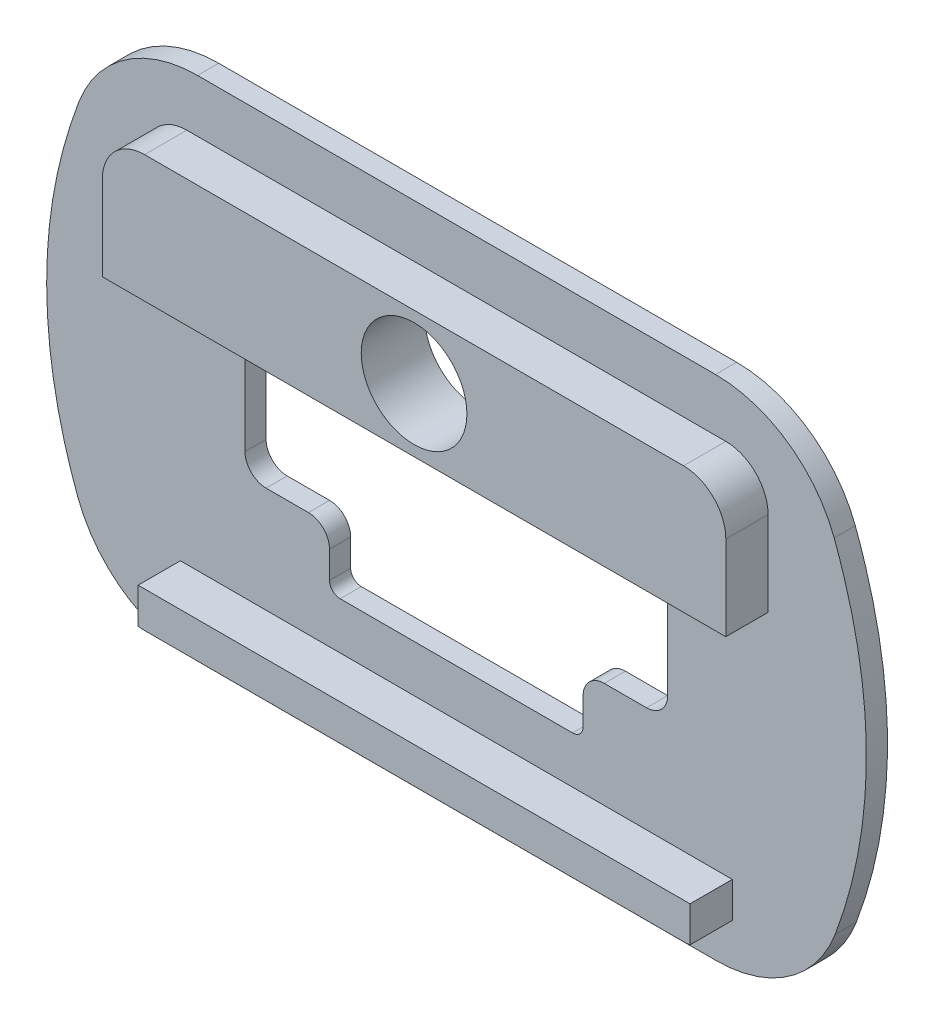
SolidWorks part; units mm, degrees
ref_plane "Front Plane" through (0, 0, 0) normal (0, 0, 1) x (1, 0, 0)
ref_plane "Top Plane" through (0, 0, 0) normal (0, 1, 0) x (1, 0, 0)
ref_plane "Right Plane" through (0, 0, 0) normal (1, 0, 0) x (0, 0, -1)
sketch "Sketch1" plane through (0, 0, 0) normal (0, 0, 1) x (1, 0, 0)
  line L0 (-11.9284, 3.1923) -> (13.5716, 3.1923)
  line L1 (-13.9284, 6.9272) -> (-13.9284, 20.6923)
  line L2 (-11.9284, 22.6923) -> (13.5716, 22.6923)
  line L3 (15.5716, 6.9272) -> (15.5716, 20.6923)
  line L4 (-13.9284, 22.6923) -> (0.9376, 12.8656) construction
  line L7 (-17.0825, 24.7341) -> (-13.2392, 22.2028) construction
  line L8 (0.8216, 1.1923) -> (0.8216, 25.1923) construction
  line L9 (0.8216, 25.1923) -> (0.8216, 3.1923) construction
  line L10 (14.5325, 3.8791) -> (15.5716, 3.1923) construction
  line L11 (0.9376, 12.8656) -> (17.6599, 1.8519) construction
  line L28 (-13.9284, 6.9272) -> (-12.7351, 6.9272)
  line L34 (0.8216, 21.9694) -> (0.8216, 1.9694) construction
  line L35 (-12.2351, 6.4272) -> (-12.2351, 3.2159)
  line L37 (15.5716, 6.9272) -> (14.3784, 6.9272)
  line L38 (13.8784, 6.4272) -> (13.8784, 3.2159)
  arc A0 (13.8784, 3.2159) -> (13.5716, 3.1923) centre (13.5716, 5.1923) cw
  arc A1 (-12.2351, 3.2159) -> (-11.9284, 3.1923) centre (-11.9284, 5.1923) ccw
  arc A2 (-11.9284, 22.6923) -> (-13.9284, 20.6923) centre (-11.9284, 20.6923) ccw
  arc A3 (13.5716, 22.6923) -> (15.5716, 20.6923) centre (13.5716, 20.6923) cw
  arc A18 (-12.7351, 6.9272) -> (-12.2351, 6.4272) centre (-12.7351, 6.4272) cw
  arc A19 (14.3784, 6.9272) -> (13.8784, 6.4272) centre (14.3784, 6.4272) ccw
  point P20 (-12.2351, 22.6923)
  dimension "D5" = 2
  dimension "D6" = 0.5
  dimension "D2" = 29.5
  dimension "D4" = 19.5
sketch "Sketch2" plane through (0, 0, 0) normal (0, 0, 1) x (1, 0, 0)
  line L0 (-4.6784, 7.121) -> (6.3216, 7.121)
  line L1 (-8.1784, 15.9243) -> (9.8216, 15.9243)
  line L2 (-5.1784, 7.621) -> (-5.1784, 8.901)
  line L3 (-9.1784, 14.9243) -> (-9.1784, 10.901)
  line L4 (-8.1784, 9.901) -> (-6.1784, 9.901)
  line L5 (9.8216, 9.901) -> (7.8216, 9.901)
  line L6 (10.8216, 14.9243) -> (10.8216, 10.901)
  line L7 (6.8216, 7.621) -> (6.8216, 8.901)
  line L8 (0.8216, 15.9243) -> (0.8216, 7.121) construction
  line L9 (10.8216, 12.9126) -> (-9.1784, 12.9126) construction
  arc A0 (-5.1784, 8.901) -> (-6.1784, 9.901) centre (-6.1784, 8.901) ccw
  arc A1 (7.8216, 9.901) -> (6.8216, 8.901) centre (7.8216, 8.901) ccw
  arc A2 (-9.1784, 10.901) -> (-8.1784, 9.901) centre (-8.1784, 10.901) ccw
  arc A3 (9.8216, 9.901) -> (10.8216, 10.901) centre (9.8216, 10.901) ccw
  arc A4 (-9.1784, 14.9243) -> (-8.1784, 15.9243) centre (-8.1784, 14.9243) cw
  arc A5 (9.8216, 15.9243) -> (10.8216, 14.9243) centre (9.8216, 14.9243) cw
  arc A6 (-4.6784, 7.121) -> (-5.1784, 7.621) centre (-4.6784, 7.621) cw
  arc A7 (6.8216, 7.621) -> (6.3216, 7.121) centre (6.3216, 7.621) cw
  point P0 (3.0945, 14.452)
  point P1 (3.0945, 14.452)
  point P3 (3.0945, 14.452)
  point P5 (0.8216, 7.121)
  point P8 (0.8216, 15.9243)
  point P17 (0.8216, 12.9126)
  point P18 (0, 0)
  point P22 (0, 0)
  point P30 (-9.1784, 15.9243)
  point P33 (10.8216, 15.9243)
  point P34 (0, 0)
  point P39 (0, 0)
  dimension "D2" = 1
  dimension "D3" = 0.5
  dimension "D1" = 20
sketch "Sketch4" plane through (0, 0, 0) normal (0, 0, 1) x (1, 0, 0)
  line L0 (-11.47, 1.1896) -> (13.1295, 1.1896)
  line L1 (-11.4218, 25.1896) -> (13.0813, 25.1896)
  arc A0 (-11.4218, 25.1896) -> (-17.0387, 21.2993) centre (-11.4218, 19.1896) ccw
  arc A1 (-11.47, 1.1896) -> (-17.0866, 5.0793) centre (-11.47, 7.1896) cw
  arc A2 (13.0813, 25.1896) -> (18.6982, 21.2993) centre (13.0813, 19.1896) cw
  arc A3 (13.1295, 1.1896) -> (18.7461, 5.0793) centre (13.1295, 7.1896) ccw
  spline S0 degree 3 poles (-17.0866, 5.0793) (-18.0777, 7.717) (-19.0613, 13.218) (-18.0465, 18.6161) (-17.0387, 21.2993) knots 0.167422 0.167422 0.167422 0.167422 0.502499 0.837905 0.837905 0.837905 0.837905
  spline S1 degree 3 poles (18.7461, 5.0793) (19.7372, 7.717) (20.7208, 13.218) (19.706, 18.6161) (18.6982, 21.2993) knots 0.167422 0.167422 0.167422 0.167422 0.502499 0.837905 0.837905 0.837905 0.837905
extrude "Boss-Extrude1" add sketch "Sketch4" along normal blind 1
extrude "Boss-Extrude2" add sketch "Sketch1" along normal blind 3
extrude "Cut-Extrude3" cut sketch "Sketch2" along normal blind 3
sketch "Sketch6" plane through (0, 0, 3) normal (0, 0, 1) x (1, 0, 0)
  circle A0 centre (0.8216, 19.6851) radius 2.5
  point P2 (0.8355, 19.7835)
  point P3 (0.8216, 19.6851)
  dimension "D1" = 5
sketch "Sketch7" plane through (0, 0, 3) normal (0, 0, 1) x (1, 0, 0)
  line L0 (-13.9284, 20.6923) -> (-13.9284, 6.9272) construction
  line L1 (-13.9284, 16.6874) -> (15.7858, 16.6874)
  line L2 (-13.9284, 16.6874) -> (-13.9284, 4.8974)
  line L3 (-13.9284, 4.8974) -> (15.7858, 4.8974)
  line L4 (15.7858, 16.6874) -> (15.7858, 4.8974)
extrude "Cut-Extrude4" cut sketch "Sketch7" against normal blind 2
extrude "Cut-Extrude5" cut sketch "Sketch6" against normal through all both and the other way through all contours A0
